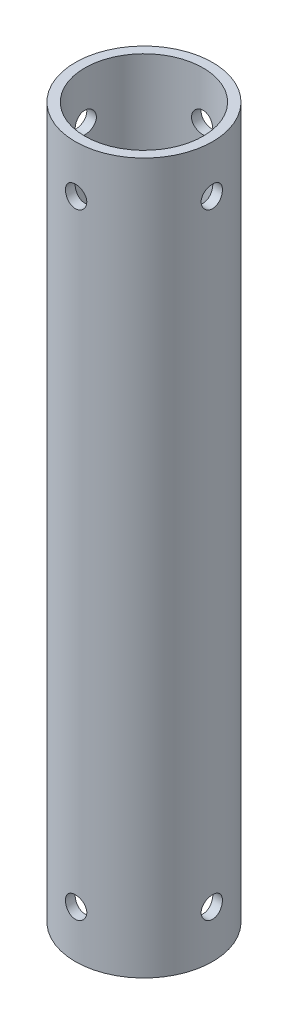
SolidWorks part; units mm, degrees
material "6061-T6 (SS)"
ref_plane "Front Plane" through (0, 0, 0) normal (0, 0, 1) x (1, 0, 0)
ref_plane "Top Plane" through (0, 0, 0) normal (0, 1, 0) x (1, 0, 0)
ref_plane "Right Plane" through (0, 0, 0) normal (1, 0, 0) x (0, 0, -1)
sketch "Sketch1" plane through (0, 0, 0) normal (0, 1, 0) x (1, 0, 0)
  circle A0 centre (0, 0) radius 12.5
  circle A1 centre (0, 0) radius 14.5
  dimension "D1" = 25
  dimension "D2" = 29
extrude "Boss-Extrude1" add sketch "Sketch1" along normal blind 150
sketch "Sketch2" plane through (0, 0, 0) normal (0, 0, 1) x (1, 0, 0)
  line L0 (0, 150) -> (0, 112.6118) construction
  line L1 (12.5, 150) -> (-12.5, 150) construction
  line L2 (0, 0) -> (0, 23.5971) construction
  line L3 (-14.5, 0) -> (14.5, 0) construction
  circle A0 centre (0, 140) radius 2.25
  circle A1 centre (0, 10) radius 2.25
  dimension "D1" = 4.5
  dimension "D3" = 4.5
  dimension "D2" = 10
  dimension "D4" = 10
extrude "Cut-Extrude1" cut sketch "Sketch2" against normal through all both and the other way through all
pattern_circular "CirPattern1" count 4 over 360 about axis through (0, 150, 0) along (0, -1, 0) of "Cut-Extrude1"
